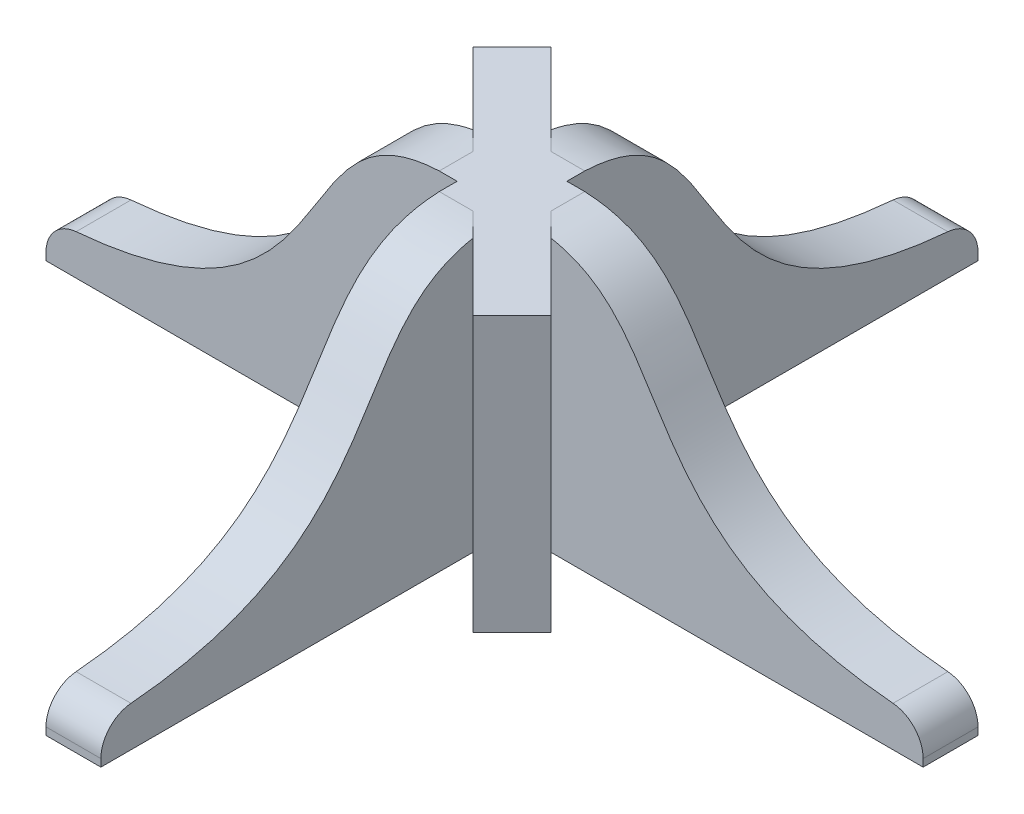
SolidWorks part; units mm, degrees
ref_plane "Front Plane" through (0, 0, 0) normal (0, 0, 1) x (1, 0, 0)
ref_plane "Top Plane" through (0, 0, 0) normal (0, 1, 0) x (1, 0, 0)
ref_plane "Right Plane" through (0, 0, 0) normal (1, 0, 0) x (0, 0, -1)
sketch "Sketch3" plane through (0, 0, 0) normal (0, 1, 0) x (1, 0, 0)
  line L1 (-15, 2.5) -> (15, 2.5)
  line L2 (-15, 2.5) -> (-15, -2.5)
  line L3 (-15, -2.5) -> (15, -2.5)
  line L4 (15, 2.5) -> (15, -2.5)
  line L5 (-15, 2.5) -> (15, -2.5) construction
  line L6 (-15, -2.5) -> (15, 2.5) construction
  line L7 (-2.5, -15) -> (2.5, -15)
  line L8 (-2.5, -15) -> (-2.5, 15)
  line L9 (-2.5, 15) -> (2.5, 15)
  line L10 (2.5, -15) -> (2.5, 15)
  line L11 (-2.5, -15) -> (2.5, 15) construction
  line L12 (-2.5, 15) -> (2.5, -15) construction
  point P0 (0, 0)
  point P6 (0, 0)
  dimension "D1" = 5
  dimension "D2" = 5
  dimension "D3" = 30
  dimension "D4" = 30
extrude "Boss-Extrude2" add sketch "Sketch3" along normal blind 25 contours L1 L10 L9 L8 | L3 L10 L1 L8 | L3 L8 L1 L2 | L10 L3 L4 L1
sketch "Sketch4" plane through (2.5, 0, 0) normal (1, 0, 0) x (0, 0, -1)
  line L0 (-2.5, 0) -> (-39.9546, 0)
  line L1 (-39.9546, 0) -> (-39.9546, 3.5)
  line L3 (-2.5, 25) -> (-2.5, 0) construction
  line L4 (-15, 17.3574) -> (-15, 25)
  line L5 (-15, 25) -> (-15, 0) construction
  line L6 (-15, 25) -> (-2.5, 25)
  line L7 (-2.5, 0) -> (-2.5, 25) construction
  line L8 (-15, 25) -> (-2.5, 25) construction
  spline S0 degree 3 poles (-39.9546, 3.5) (-10.3989, 4.5907) (-19.5926, 25.714) (-2.5, 25) knots 0 0 0 0 1 1 1 1
  point P6 (0, 0)
  point P7 (-2.5, 0)
  point P16 (-2.5, 0)
  point P17 (-2.5, 25)
  line M9 (-15, 25) -> (-15, 0)
  dimension "D2" = 37.4546
  dimension "D1" = 3.5
extrude "Cut-Extrude2" cut sketch "Sketch4" against normal through all both and the other way through all contours S0 L6 M9
sketch "Sketch5" plane through (2.5, 0, 0) normal (1, 0, 0) x (0, 0, -1)
  line L0 (-2.5, 0) -> (-39.9546, 0) construction
  line L1 (-39.9546, 0) -> (-39.9546, 3.5) construction
  line L2 (-15, 25) -> (-2.5, 25) construction
  line L4 (-2.5, 0) -> (-39.9546, 0)
  line L5 (-39.9546, 0) -> (-39.9546, 3.5)
  line L6 (-4.1276, 25) -> (-2.5, 25)
  line L7 (-2.5, 25) -> (-2.5, 0)
  line L8 (-15, 17.3574) -> (-15, 0)
  spline S0 degree 3 poles (-1817.1687, 918.2125) (1670.8433, -1068.781) (-1663.1325, 1164.0196) (1671.7026, -1068.7688) knots -2.39761 -2.39761 -2.39761 -2.39761 3.522033 3.522033 3.522033 3.522033 only from (-39.9546, 3.5) to (-2.5, 25) construction
  spline S1 degree 3 poles (-39.9546, 3.5) (-10.3989, 4.5907) (-19.5926, 25.714) (-2.5, 25) knots 0 0 0 0 1 1 1 1
  point P8 (-15, 0)
  line M7 (-15, 17.3574) -> (-15, 0)
extrude "Boss-Extrude3" add sketch "Sketch5" against normal up to surface (5 mm away) contours S1 L5 L4 M7 up to face at (-2.5, 14.2357, 6.7383)
mirror "Mirror1" about plane through (0, 0, 0) normal (0, 0, 1) of "Boss-Extrude3"
mirror "Mirror2" about plane through (0, 0, 0) normal (0, 0, 1) of "Cut-Extrude2"
sketch "Sketch9" plane through (0, 25, 0) normal (0, 1, 0) x (1, 0, 0)
  line L1 (-15, 2.5) -> (-2.5, 2.5)
  line L2 (-15, 2.5) -> (-15, -2.5)
  line L3 (-15, -2.5) -> (-2.5, -2.5)
  line L4 (-2.5, 2.5) -> (-2.5, -2.5)
  line L5 (2.5, 2.5) -> (15, 2.5)
  line L6 (2.5, 2.5) -> (2.5, -2.5)
  line L7 (2.5, -2.5) -> (15, -2.5)
  line L8 (15, 2.5) -> (15, -2.5)
extrude "Cut-Extrude3" cut sketch "Sketch9" against normal through all
pattern_circular "CirPattern9" count 4 over 360 about axis through (0, 0, 0) along (0, 1, 0) of bodies 110
ref_plane "Plane1" through (0, 0, 0) normal (-0.7071, 0, 0.7071) x (0.7071, 0, 0.7071)
sketch "Sketch11" plane through (0, 0, 0) normal (-0.7071, 0, 0.7071) x (0.7071, 0, 0.7071)
  line L0 (26.4844, 0) -> (-30.0199, 0) construction
  line L1 (-15, 25) -> (15, 25)
  line L2 (-15, 25) -> (-15, 0)
  line L3 (-15, 0) -> (15, 0)
  line L4 (15, 25) -> (15, 0)
  dimension "D1" = 30
  dimension "D2" = 25
extrude "Boss-Extrude5" add sketch "Sketch11" along normal mid plane 5
fillet "Fillet1" radius 3 8 edges at (0, 3.5, 39.9546) (0, 3.5, -39.9546) (39.9546, 3.5, 0) (-39.9546, 3.5, 0)
equation "\"Length\"= 25.33"
equation "\"Width\"= 1.6"
equation "\"Tolerance\"= 0.15"
equation "\"Slot Length\"= \"Length\" + \"Tolerance\""
equation "\"Slot Width\"= \"Width\" + \"Tolerance\""
